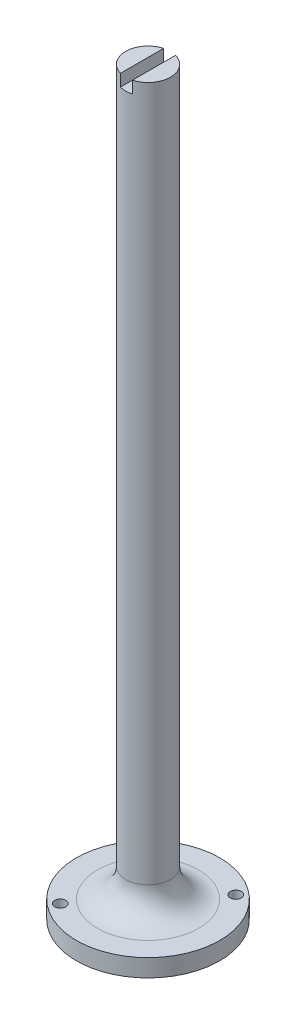
SolidWorks part; units mm, degrees
material "AISI 316 Annealed Stainless Steel Bar (SS)"
ref_plane "Front Plane" through (0, 0, 0) normal (0, 0, 1) x (1, 0, 0)
ref_plane "Top Plane" through (0, 0, 0) normal (0, 1, 0) x (1, 0, 0)
ref_plane "Right Plane" through (0, 0, 0) normal (1, 0, 0) x (0, 0, -1)
sketch "Sketch1" plane through (0, 0, 0) normal (0, 0, 1) x (1, 0, 0)
  line L0 (0, -31.8317) -> (0, 0) construction
  line L1 (0, 0) -> (10.16, 0)
  line L2 (10.16, 0) -> (10.16, 2.5)
  line L4 (3.175, 2.5) -> (3.175, 105)
  line L5 (3.175, 105) -> (0, 105)
  line L7 (0, 105) -> (0, 0)
  line L8 (10.16, 2.5) -> (3.175, 2.5)
  dimension "D1" = 10.16
  dimension "D2" = 3.175
  dimension "D3" = 2.5
  dimension "D4" = 105
revolve "Revolve1" add sketch "Sketch1" angle 360 about L0
cosmetic thread "Cosmetic Thread1" parameters "D1"=12, "D2"=5.268
sketch "Sketch2" [suppressed] plane through (0, 2.5, 0) normal (0, 1, 0) x (1, 0, 0)
  line L0 (-0.75, 10.1323) -> (-0.75, 0)
  line L1 (-0.75, 0) -> (0.75, 0)
  line L2 (0.75, 0) -> (0.75, 10.1323)
  circle A0 centre (0, 0) radius 10.16 construction
  arc A1 (0.75, 10.1323) -> (-0.75, 10.1323) centre (0, 0) ccw
  point P7 (0, 0)
  dimension "D1" = 1.5
extrude "Boss-Extrude1" [suppressed] add sketch "Sketch2" along normal blind 12
pattern_circular "CirPattern1" [suppressed] count 3 over 360
sketch "Sketch3" [suppressed] plane through (0, 14.5, 0) normal (0, 1, 0) x (1, 0, 0)
  circle A0 centre (0, 0) radius 7.475
  dimension "D1" = 14.95
extrude "Cut-Extrude2" [suppressed] cut sketch "Sketch3" against normal up to surface (12 mm away) flip side to cut
fillet "Fillet1" radius 4 1 edges at (0, 2.5, -3.175)
sketch "Sketch4" plane through (0, 0, 0) normal (0, 0, 1) x (1, 0, 0)
  line L0 (3.175, 105) -> (-3.175, 105) construction
  line L1 (-0.85, 105) -> (0.85, 105)
  line L2 (-0.85, 105) -> (-0.85, 103.3)
  line L3 (-0.85, 103.3) -> (0.85, 103.3)
  line L4 (0.85, 105) -> (0.85, 103.3)
  line L5 (0, 103.3) -> (0, 0) construction
  dimension "D1" = 1.7
  dimension "D2" = 1.7
extrude "Cut-Extrude3" cut sketch "Sketch4" against normal through all both and the other way through all
hole_wizard "1/16 (0.0625) Dowel Hole1" positions "Sketch5" profile "Sketch6" hole size "1/16" standard "ANSI Inch"
sketch "Sketch5" plane through (0, 0, 0) normal (0, -1, 0) x (-1, 0, 0)
  point P0 (5.675, -6.7648)
  point P3 (-5.675, 6.7648)
sketch "Sketch6" plane through (-5.675, 0, 6.7648) normal (1, 0, 0) x (0, 0, -1)
  line L0 (0, 0) -> (0, 6.4769)
  line L1 (0, 6.4769) -> (0.7937, 6)
  line L2 (0.7937, 6) -> (0.7937, 0)
  line L5 (0.7937, 0) -> (0, 0)
  line L10 (0, 6.4769) -> (-0.7937, 6) construction
  line L11 (0, -6.35) -> (0, 107.95) construction
  dimension "Hole Dia." = 1.5875
  dimension "Hole Depth" = 6
  dimension "Drill Angle" = 118
